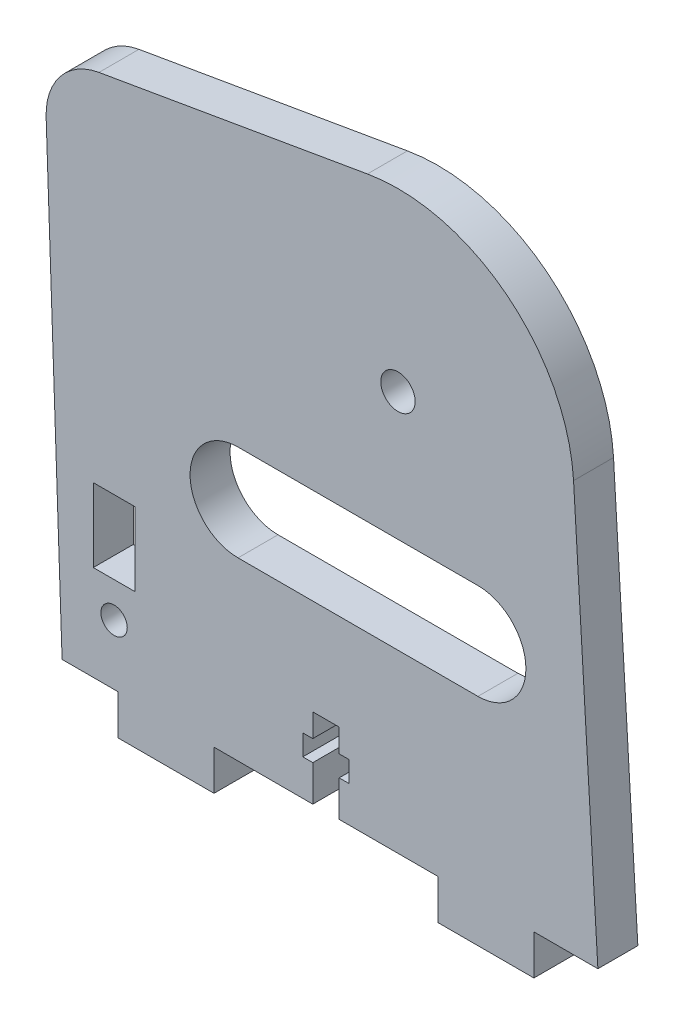
SolidWorks part; units mm, degrees
ref_plane "Спереди" through (0, 0, 0) normal (0, 0, 1) x (1, 0, 0)
ref_plane "Сверху" through (0, 0, 0) normal (0, 1, 0) x (1, 0, 0)
ref_plane "Справа" through (0, 0, 0) normal (1, 0, 0) x (0, 0, -1)
other "Configuration Table"
sketch "Eskiz_kontur" plane through (0, 0, 0) normal (0, 0, 1) x (1, 0, 0)
  line L0 (21.959, 51.3431) -> (25, 0)
  line L1 (-37.3892, 65.8785) -> (-3.8203, 71.6658)
  line L2 (25, 0) -> (17, 0)
  line L3 (17, 0) -> (17, -5)
  line L4 (-42, 0) -> (-43.9951, 57.7208)
  line L5 (17, -5) -> (5, -5)
  line L6 (-35, 0) -> (-42, 0)
  line L7 (5, -5) -> (5, 0)
  line L8 (-35, -5) -> (-35, 0)
  line L9 (5, 0) -> (-7.35, 0)
  line L10 (-23, -5) -> (-35, -5)
  line L11 (-7.35, 0) -> (-7.35, 4.5)
  line L12 (-23, 0) -> (-23, -5)
  line L13 (-7.35, 4.5) -> (-6.1, 4.5)
  line L14 (-10.65, 0) -> (-23, 0)
  line L15 (-6.1, 4.5) -> (-6.1, 7.1)
  line L16 (-10.65, 4.5) -> (-10.65, 0)
  line L17 (-6.1, 7.1) -> (-7.35, 7.1)
  line L18 (-11.9, 4.5) -> (-10.65, 4.5)
  line L19 (-7.35, 7.1) -> (-7.35, 10)
  line L20 (-11.9, 7.1) -> (-11.9, 4.5)
  line L21 (-7.35, 10) -> (-10.65, 10)
  line L22 (-10.65, 7.1) -> (-11.9, 7.1)
  line L23 (-10.65, 10) -> (-10.65, 7.1)
  line L24 (-32.9, 11.9) -> (-32.9, 21.1)
  line L25 (-32.9, 21.1) -> (-38.1, 21.1)
  line L26 (-38.1, 11.9) -> (-32.9, 11.9)
  line L27 (-38.1, 21.1) -> (-38.1, 11.9)
  line L28 (10, 34) -> (-20, 34)
  line L29 (-20, 22) -> (10, 22)
  arc A0 (-3.8203, 71.6658) -> (21.959, 51.3431) centre (0, 50) cw
  arc A1 (-43.9951, 57.7208) -> (-37.3892, 65.8785) centre (-36, 58) cw
  arc A2 (-20, 34) -> (-20, 22) centre (-20, 28) ccw
  arc A3 (10, 22) -> (10, 34) centre (10, 28) ccw
extrude "Plastina" add sketch "Eskiz_kontur" along normal blind 5
sketch "Eskiz_otverstiya" plane through (0, 0, 0) normal (0, 0, 1) x (1, 0, 0)
  circle A0 centre (-35.5, 7.5) radius 1.65
  circle A1 centre (0, 50) radius 2.15
  dimension "d1" = 3.3
  dimension "d2" = 4.3
extrude "Otverstiya" cut sketch "Eskiz_otverstiya" against normal through all and the other way through all
equation "\"T3\" = 3"
equation "\"T5\" = 5"
equation "\"D_M3\" = 3.3"
equation "\"D_M2\" = 2.2"
equation "\"D_M3_TAP\" = 2.5"
equation "\"D_M4\" = 4.5"
equation "\"L1\" = 100"
equation "\"L2\" = 100"
equation "\"D1@Plastina\" = \"T5\""
equation "\"d1@Eskiz_otverstiya\" = \"D_M3\""
